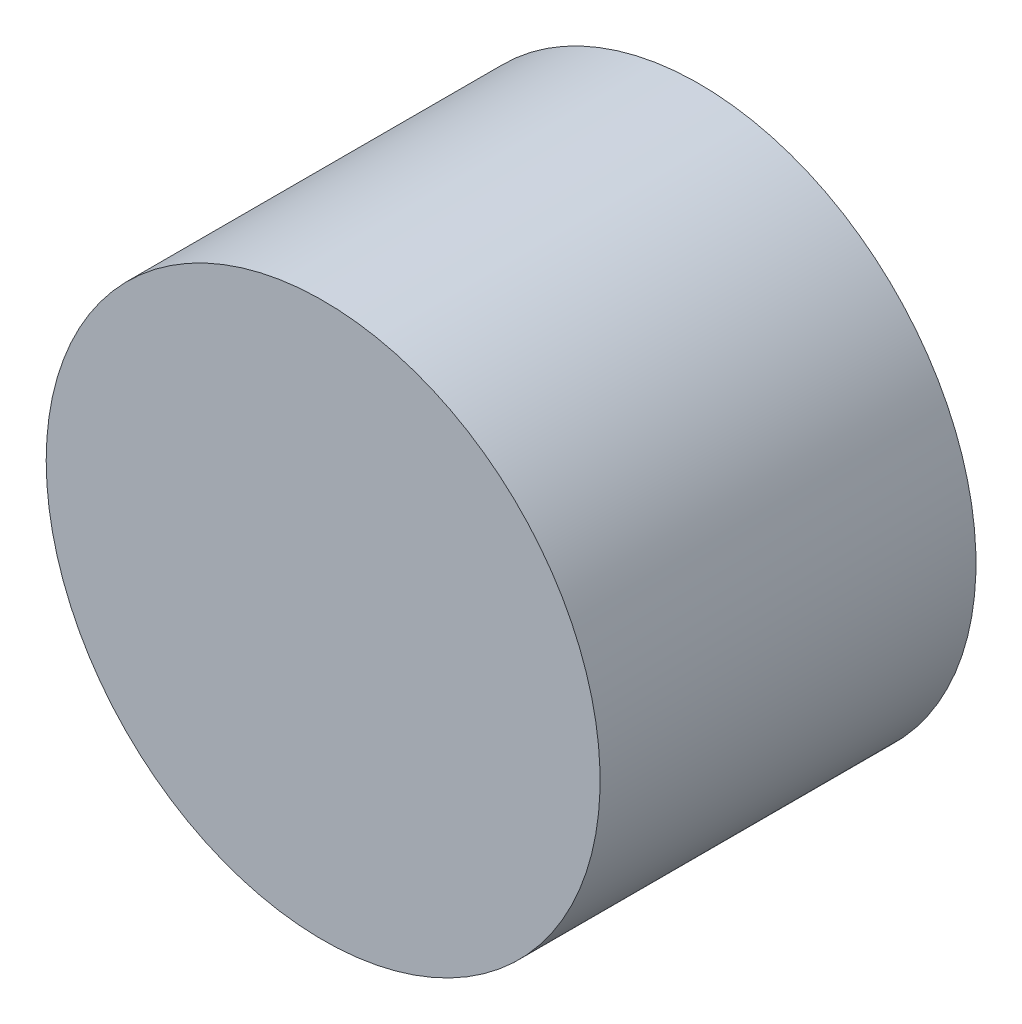
SolidWorks part; units mm, degrees
ref_plane "Спереди" through (0, 0, 0) normal (0, 0, 1) x (1, 0, 0)
ref_plane "Сверху" through (0, 0, 0) normal (0, 1, 0) x (1, 0, 0)
ref_plane "Справа" through (0, 0, 0) normal (1, 0, 0) x (0, 0, -1)
sketch "Эскиз1" plane through (0, 0, 0) normal (0, 0, 1) x (1, 0, 0)
  circle A0 centre (0, 0) radius 2.8
  dimension "D1" = 5.6
extrude "Бобышка-Вытянуть1" add sketch "Эскиз1" along normal blind 3.8
